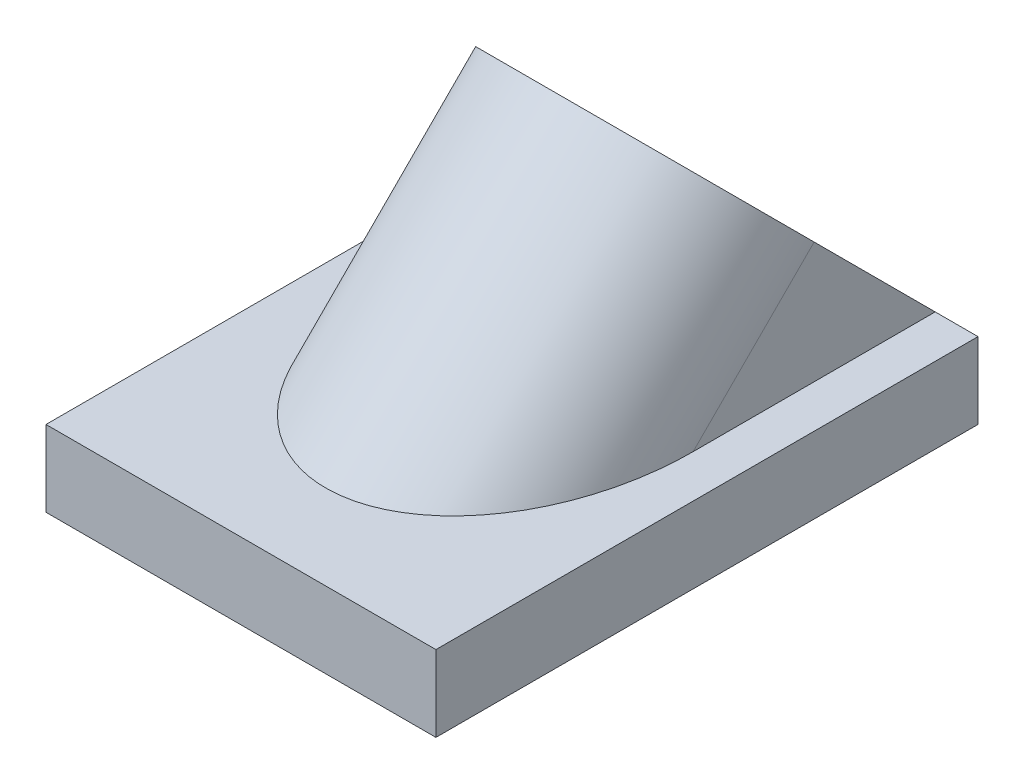
SolidWorks part; units mm, degrees
ref_plane "前视基准面" through (0, 0, 0) normal (0, 0, 1) x (1, 0, 0)
ref_plane "上视基准面" through (0, 0, 0) normal (0, 1, 0) x (1, 0, 0)
ref_plane "右视基准面" through (0, 0, 0) normal (1, 0, 0) x (0, 0, -1)
other "Configuration Table"
sketch "草图1" plane through (0, 0, 0) normal (1, 0, 0) x (0, 0, -1)
  line L1 (-28.5, -8) -> (28.5, -8)
  line L2 (-28.5, -8) -> (-28.5, 0)
  line L3 (-28.5, 0) -> (28.5, 0)
  line L4 (28.5, -8) -> (28.5, 0)
  point P0 (0, -4)
  dimension "D1" = 8
  dimension "D2" = 57
extrude "凸台-拉伸1" add sketch "草图1" against normal blind 41
ref_plane "基准面1" through (0, 14.25, -14.25) normal (0, 0.7071, -0.7071) x (1, 0, 0)
sketch "草图2" plane through (0, 14.25, -14.25) normal (0, 0.7071, -0.7071) x (1, 0, 0)
  line L0 (-20.5, 20.1525) -> (-20.5, -5.1759) construction
  line L1 (-41, 20.1525) -> (-41, -20.1525) construction
  line L3 (-41, 20.1525) -> (0, 20.1525) construction
  line L4 (-36.5, 2.1525) -> (-36.5, 20.1525)
  line L5 (-4.5, 2.1525) -> (-4.5, 20.1525)
  line L6 (-4.5, 20.1525) -> (-36.5, 20.1525)
  arc A0 (-36.5, 2.1525) -> (-4.5, 2.1525) centre (-20.5, 2.1525) ccw
  dimension "D2" = 32
  dimension "D1" = 20.5
  dimension "D3" = 18
extrude "凸台-拉伸2" add sketch "草图2" against normal up to next
sketch "草图3" plane through (0, 14.25, -14.25) normal (0, 0.7071, -0.7071) x (1, 0, 0)
  circle A0 centre (-20.5, 2.1525) radius 8
  dimension "D1" = 16
extrude "切除-拉伸1" cut sketch "草图3" against normal blind 41
